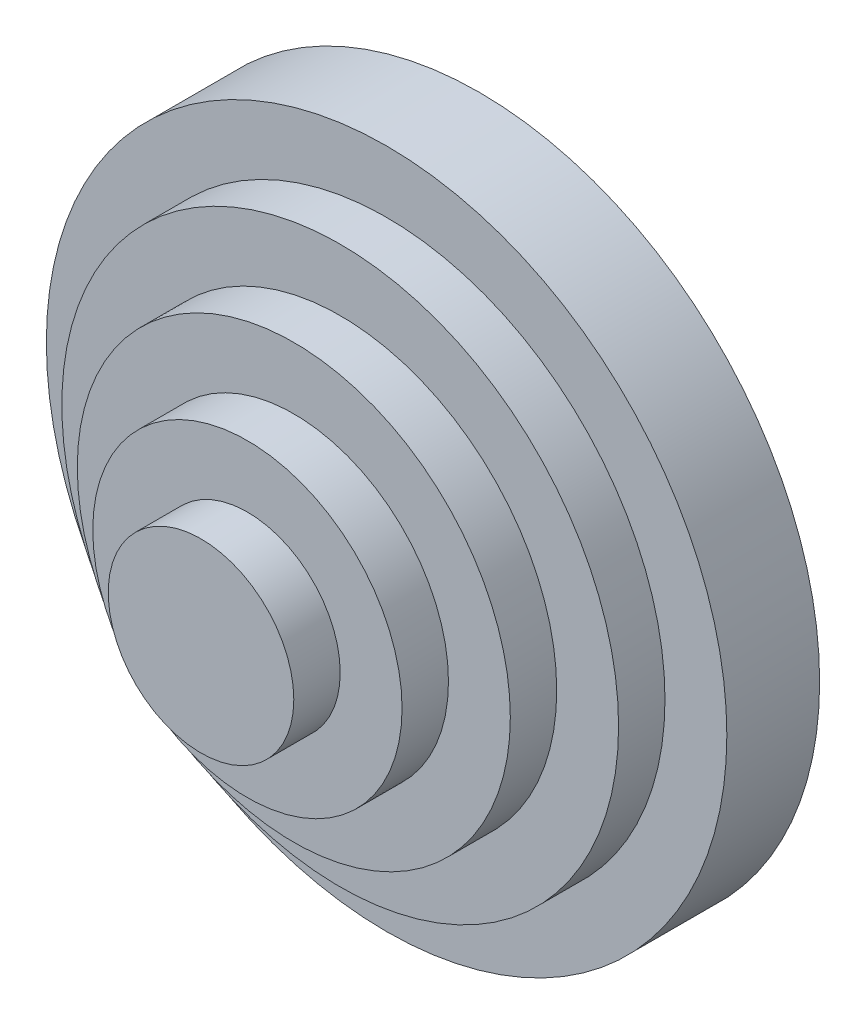
SolidWorks part; units mm, degrees
ref_plane "Спереди" through (0, 0, 0) normal (0, 0, 1) x (1, 0, 0)
ref_plane "Сверху" through (0, 0, 0) normal (0, 1, 0) x (1, 0, 0)
ref_plane "Справа" through (0, 0, 0) normal (1, 0, 0) x (0, 0, -1)
sketch "Sketch1" plane through (0, 0, 0) normal (0, 0, 1) x (1, 0, 0)
  line L8 (2.2249, 4.7) -> (-2.2249, 4.7)
  line L9 (-4.7, 2.2249) -> (-4.7, -2.2249)
  line L10 (-2.2249, -4.7) -> (2.2249, -4.7)
  line L11 (4.7, -2.2249) -> (4.7, 2.2249)
  line L12 (2.2249, 4.7) -> (-2.2249, 4.7)
  line L13 (-4.7, 2.2249) -> (-4.7, -2.2249)
  line L14 (-2.2249, -4.7) -> (2.2249, -4.7)
  line L15 (4.7, -2.2249) -> (4.7, 2.2249)
  circle A4 centre (0, 0) radius 11
  arc A8 (4.7, 2.2249) -> (2.2249, 4.7) centre (0, 0) ccw
  arc A9 (-2.2249, 4.7) -> (-4.7, 2.2249) centre (0, 0) ccw
  arc A10 (-4.7, -2.2249) -> (-2.2249, -4.7) centre (0, 0) ccw
  arc A11 (2.2249, -4.7) -> (4.7, -2.2249) centre (0, 0) ccw
  arc A12 (4.7, 2.2249) -> (2.2249, 4.7) centre (0, 0) ccw
  arc A13 (-2.2249, 4.7) -> (-4.7, 2.2249) centre (0, 0) ccw
  arc A14 (-4.7, -2.2249) -> (-2.2249, -4.7) centre (0, 0) ccw
  arc A15 (2.2249, -4.7) -> (4.7, -2.2249) centre (0, 0) ccw
  dimension "D2" = 22
  dimension "D1" = 0.2
extrude "Extrude1" add sketch "Sketch1" against normal blind 3
sketch "Sketch2" plane through (0, 0, 0) normal (0, 0, 1) x (1, 0, 0)
  circle A0 centre (0, 0) radius 9
  circle A1 centre (0, 0) radius 11 construction
  dimension "D1" = 2
extrude "Extrude2" add sketch "Sketch2" along normal blind 1.5
sketch "Sketch3" plane through (0, 0, 1.5) normal (0, 0, 1) x (1, 0, 0)
  circle A2 centre (0, 0) radius 7
  circle A3 centre (0, 0) radius 7
  dimension "D1" = 2
extrude "Extrude3" add sketch "Sketch3" along normal blind 1.5
sketch "Sketch4" plane through (0, 0, 3) normal (0, 0, 1) x (1, 0, 0)
  circle A2 centre (0, 0) radius 5
  circle A3 centre (0, 0) radius 5
  dimension "D1" = 2
extrude "Extrude4" add sketch "Sketch4" along normal blind 1.5
sketch "Sketch5" plane through (0, 0, 4.5) normal (0, 0, 1) x (1, 0, 0)
  circle A2 centre (0, 0) radius 3
  circle A3 centre (0, 0) radius 3
  dimension "D1" = 2
extrude "Extrude5" add sketch "Sketch5" along normal blind 1.5
